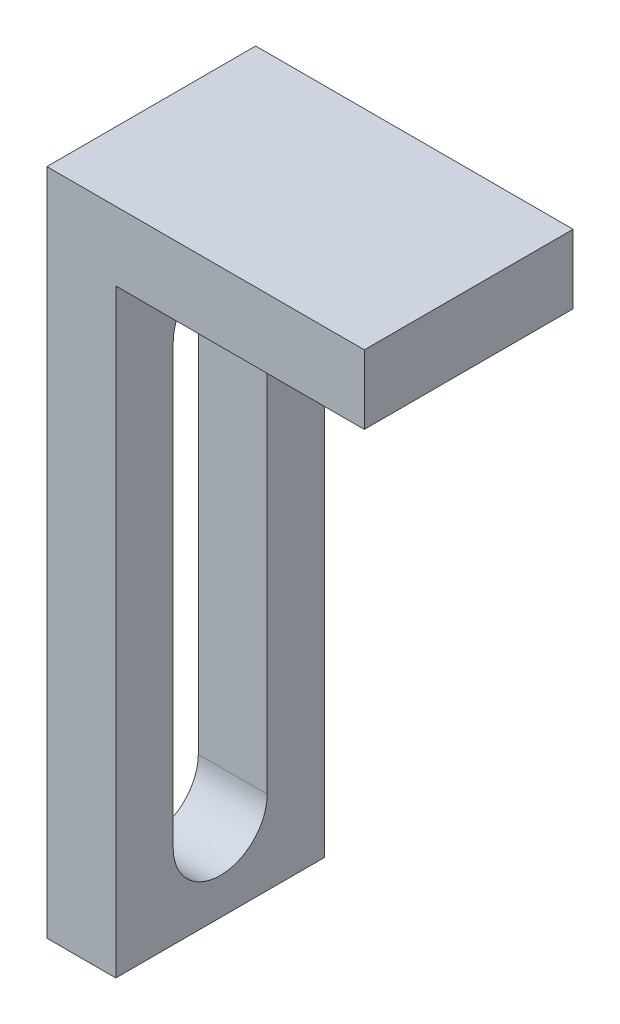
SolidWorks part; units mm, degrees
ref_plane "Front Plane" through (0, 0, 0) normal (0, 0, 1) x (1, 0, 0)
ref_plane "Top Plane" through (0, 0, 0) normal (0, 1, 0) x (1, 0, 0)
ref_plane "Right Plane" through (0, 0, 0) normal (1, 0, 0) x (0, 0, -1)
sketch "Sketch1" plane through (0, 0, 0) normal (0, 0, 1) x (1, 0, 0)
  line L1 (-10.3051, -21.6949) -> (-7.0051, -21.6949)
  line L2 (-10.3051, -21.6949) -> (-10.3051, 10.3051)
  line L3 (-10.3051, 10.3051) -> (4.8949, 10.3051)
  line L4 (4.8949, 7.0051) -> (4.8949, 10.3051)
  line L5 (-10.3051, -21.6949) -> (4.8949, 10.3051) construction
  line L6 (-10.3051, 10.3051) -> (0, 0) construction
  line L9 (4.8949, 7.0051) -> (-7.0051, 7.0051)
  line L10 (-7.0051, -21.6949) -> (-7.0051, 7.0051)
  point P0 (0, 0)
  dimension "D1" = 15.2
  dimension "D2" = 32
  dimension "D3" = 3.3
  dimension "D4" = 3.3
extrude "Boss-Extrude1" add sketch "Sketch1" along normal blind 10 contours L1 L10 L9 L4 L3 L2
sketch "Sketch2" plane through (-10.3051, 0, 0) normal (-1, 0, 0) x (0, 0, 1)
  line L0 (5, 8.241) -> (5, -17.6949) construction
  line L1 (10, 10.3051) -> (0, 10.3051) construction
  line L2 (10, -21.6949) -> (0, -21.6949) construction
  line L3 (5, -19.9449) -> (5, -49991.759) construction
  line L5 (2.75, 3.3051) -> (2.75, -17.6949)
  line L7 (7.25, 3.3051) -> (7.25, -17.6949)
  arc A0 (7.25, 3.3051) -> (2.75, 3.3051) centre (5, 3.3051) ccw
  arc A1 (2.75, -17.6949) -> (7.25, -17.6949) centre (5, -17.6949) ccw
  point P4 (5, 10.3051)
  dimension "D1" = 4
  dimension "D2" = 7
extrude "Cut-Extrude1" cut sketch "Sketch2" against normal blind 6
